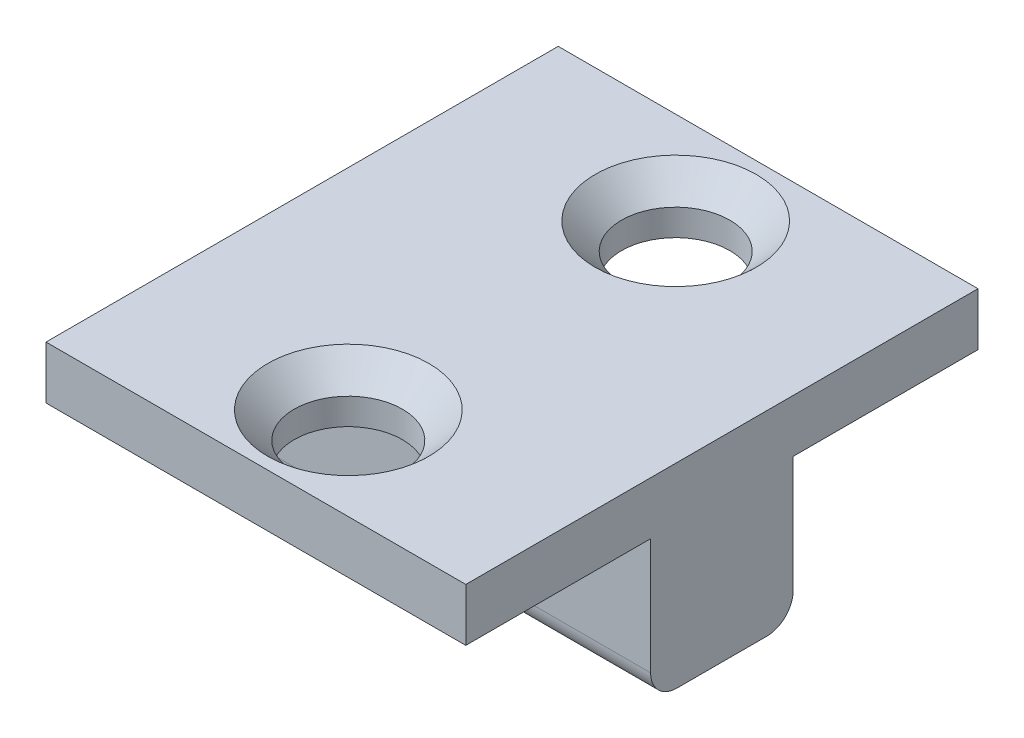
SolidWorks part; units mm, degrees
ref_plane "前视基准面" through (0, 0, 0) normal (0, 0, 1) x (1, 0, 0)
ref_plane "上视基准面" through (0, 0, 0) normal (0, 1, 0) x (1, 0, 0)
ref_plane "右视基准面" through (0, 0, 0) normal (1, 0, 0) x (0, 0, -1)
sketch "草图1" plane through (0, 0, 0) normal (0, 1, 0) x (1, 0, 0)
  line L1 (-7.95, 2.7) -> (7.95, 2.7)
  line L2 (-7.95, 2.7) -> (-7.95, -2.7)
  line L3 (-7.95, -2.7) -> (7.95, -2.7)
  line L4 (7.95, 2.7) -> (7.95, -2.7)
  line L5 (-7.95, 2.7) -> (7.95, -2.7) construction
  line L6 (-7.95, -2.7) -> (7.95, 2.7) construction
  point P0 (0, 0)
  dimension "D1" = 15.9
  dimension "D2" = 5.4
extrude "凸台-拉伸1" add sketch "草图1" along normal blind 5.4
ref_plane "基准面1" through (0, 5.4, 0) normal (0, 1, 0) x (1, 0, 0)
sketch "草图2" plane through (0, 5.4, 0) normal (0, 1, 0) x (1, 0, 0)
  line L0 (7.95, 2.7) -> (-7.95, 2.7) construction
  line L1 (7.95, 9.7) -> (-7.95, 9.7)
  line L2 (7.95, 9.7) -> (7.95, -9.7)
  line L3 (7.95, -9.7) -> (-7.95, -9.7)
  line L4 (-7.95, 9.7) -> (-7.95, -9.7)
  line L5 (7.95, 9.7) -> (-7.95, -9.7) construction
  line L6 (7.95, -9.7) -> (-7.95, 9.7) construction
  point P0 (0, 0)
  dimension "D1" = 15.9
  dimension "D2" = 7
extrude "凸台-拉伸2" add sketch "草图2" along normal blind 2
ref_plane "基准面2" through (0, 5.4, 0) normal (0, -1, 0) x (-1, 0, 0)
sketch "草图3" plane through (0, 5.4, 0) normal (0, -1, 0) x (-1, 0, 0)
  line L0 (-7.95, 6.2) -> (7.95, 6.2)
  line L1 (-7.95, 2.7) -> (-7.95, 9.7) construction
  line L2 (7.95, 9.7) -> (7.95, 2.7) construction
  line L3 (0, 9.7) -> (0, 2.7)
  line L4 (-7.95, 9.7) -> (7.95, 9.7) construction
  line L5 (-7.95, 2.7) -> (7.95, 2.7) construction
  circle A0 centre (0, 6.2) radius 2.05
extrude "切除-拉伸2" cut sketch "草图3" against normal through all contours A0
mirror "镜向2" about plane through (0, 0, 0) normal (0, 0, 1) of "切除-拉伸2"
chamfer "倒角1" distance 1 angle 45 2 edges at (0, 7.4, 8.25) (0, 7.4, -8.25)
fillet "圆角1" radius 1 2 edges at (0, 0, 2.7) (0, 0, -2.7)
